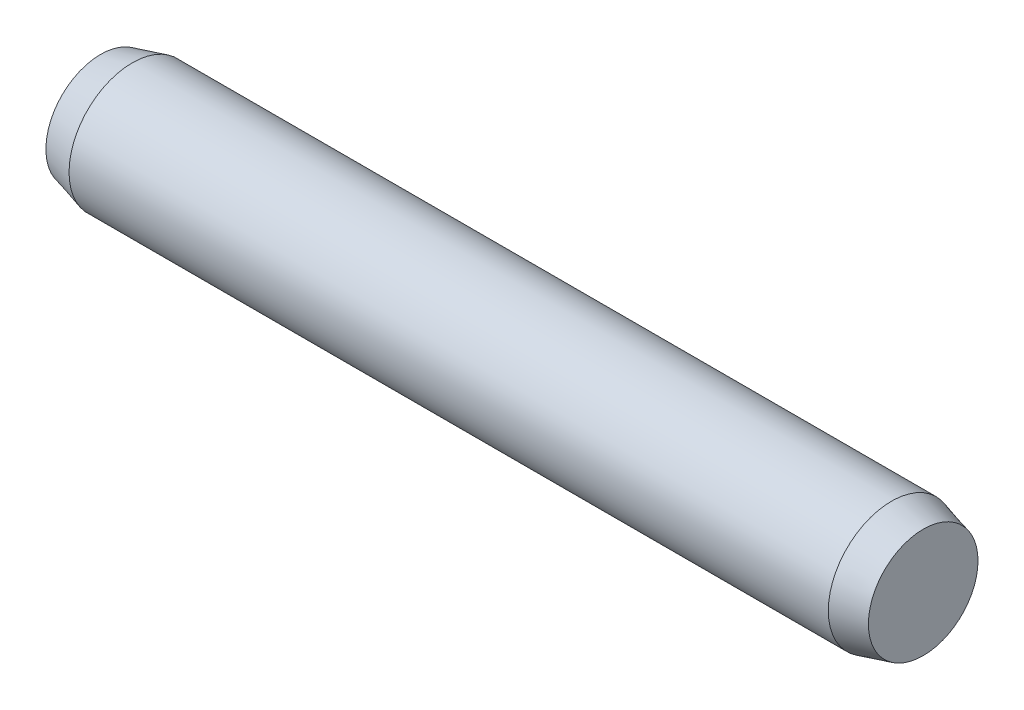
SolidWorks part; units mm, degrees
ref_plane "前视基准面" through (0, 0, 0) normal (0, 0, 1) x (1, 0, 0)
ref_plane "上视基准面" through (0, 0, 0) normal (0, 1, 0) x (1, 0, 0)
ref_plane "右视基准面" through (0, 0, 0) normal (1, 0, 0) x (0, 0, -1)
sketch "草图1" plane through (0, 0, 0) normal (1, 0, 0) x (0, 0, -1)
  circle A0 centre (0, 0) radius 2
  dimension "D1" = 4
extrude "凸台-拉伸1" add sketch "草图1" along normal blind 26
chamfer "倒角1" distance 1 angle 15 2 edges at (0, 0, -2) (26, 0, -2)
